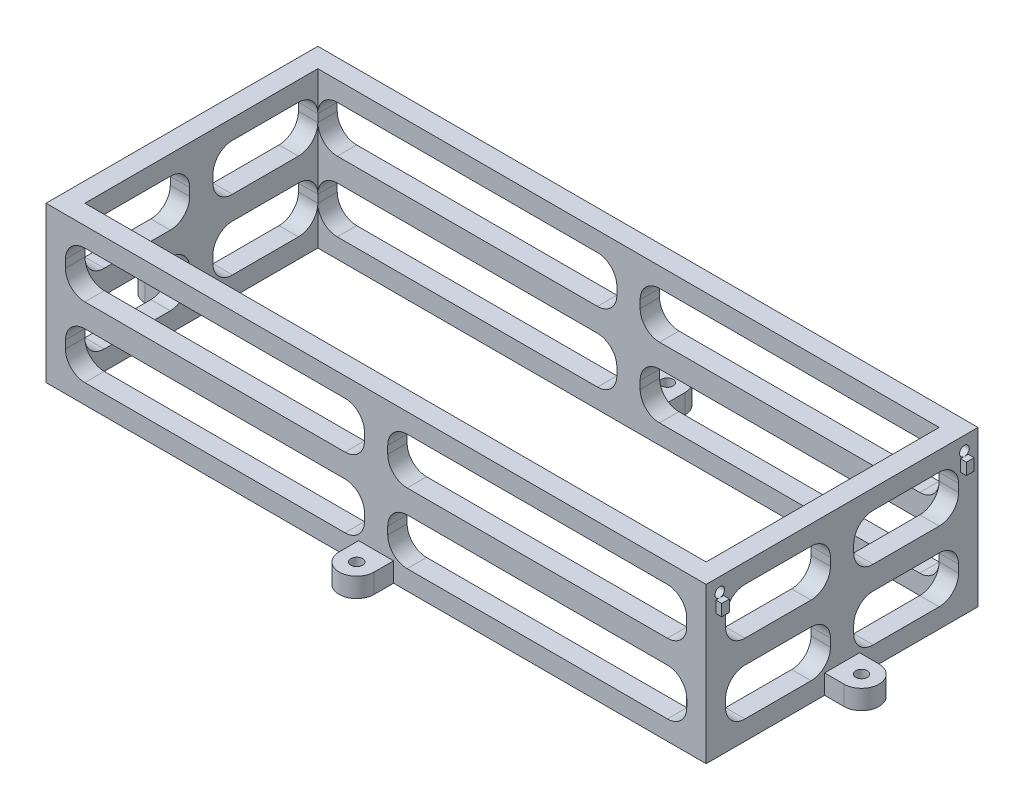
SolidWorks part; units mm, degrees
ref_plane "Front Plane" through (0, 0, 0) normal (0, 0, 1) x (1, 0, 0)
ref_plane "Top Plane" through (0, 0, 0) normal (0, 1, 0) x (1, 0, 0)
ref_plane "Right Plane" through (0, 0, 0) normal (1, 0, 0) x (0, 0, -1)
sketch "Sketch1" plane through (0, 0, 0) normal (0, 1, 0) x (1, 0, 0)
  line L1 (-85, -35) -> (85, -35)
  line L2 (-85, -35) -> (-85, 35)
  line L3 (-85, 35) -> (85, 35)
  line L4 (85, -35) -> (85, 35)
  line L5 (-85, -35) -> (85, 35) construction
  line L6 (-85, 35) -> (85, -35) construction
  point P0 (0, 0)
  dimension "D1" = 70
  dimension "D2" = 170
extrude "Boss-Extrude1" add sketch "Sketch1" along normal blind 40
shell "Shell1" thickness 5
sketch "Sketch3" plane through (-85, 0, 0) normal (-1, 0, 0) x (0, 0, 1)
  line L0 (-35, 20) -> (35, 20) construction
  line L1 (-35, 40) -> (-35, 0) construction
  line L2 (35, 40) -> (35, 0) construction
  line L3 (-35, 40) -> (35, 40) construction
  line L4 (-30, 5) -> (30, 5)
  line L5 (-30, 5) -> (-30, 35)
  line L6 (-30, 35) -> (30, 35)
  line L7 (30, 5) -> (30, 35)
  line L8 (-30, 5) -> (30, 35) construction
  line L9 (-30, 35) -> (30, 5) construction
  point P6 (0, 20)
  dimension "D1" = 5
  dimension "D2" = 5
sketch "Sketch4" plane through (85, 0, 0) normal (1, 0, 0) x (0, 0, -1)
  line L0 (0, 40) -> (0, 0) construction
  line L1 (-35, 40) -> (35, 40) construction
  line L2 (-35, 20) -> (35, 20) construction
  line L3 (-35, 40) -> (-35, 0) construction
  line L4 (35, 40) -> (35, 0) construction
  line L5 (-35, 0) -> (35, 0) construction
  line L6 (-25, 35) -> (-8, 35)
  line L7 (-30, 30) -> (-30, 28)
  line L8 (-25, 23) -> (-8, 23)
  line L9 (-3, 30) -> (-3, 28)
  line L10 (-25, 17) -> (-8, 17)
  line L11 (-30, 12) -> (-30, 10)
  line L12 (-25, 5) -> (-8, 5)
  line L13 (-3, 12) -> (-3, 10)
  line L14 (8, 35) -> (25, 35)
  line L15 (3, 30) -> (3, 28)
  line L16 (8, 23) -> (25, 23)
  line L17 (30, 30) -> (30, 28)
  line L18 (8, 17) -> (25, 17)
  line L19 (3, 12) -> (3, 10)
  line L20 (8, 5) -> (25, 5)
  line L21 (30, 12) -> (30, 10)
  arc A0 (3, 28) -> (8, 23) centre (8, 28) ccw
  arc A1 (8, 17) -> (3, 12) centre (8, 12) ccw
  arc A2 (25, 5) -> (30, 10) centre (25, 10) ccw
  arc A3 (25, 17) -> (30, 12) centre (25, 12) cw
  arc A4 (25, 23) -> (30, 28) centre (25, 28) ccw
  arc A5 (25, 35) -> (30, 30) centre (25, 30) cw
  arc A6 (8, 35) -> (3, 30) centre (8, 30) ccw
  arc A7 (3, 10) -> (8, 5) centre (8, 10) ccw
  arc A8 (-8, 5) -> (-3, 10) centre (-8, 10) ccw
  arc A9 (-8, 17) -> (-3, 12) centre (-8, 12) cw
  arc A10 (-8, 23) -> (-3, 28) centre (-8, 28) ccw
  arc A11 (-8, 35) -> (-3, 30) centre (-8, 30) cw
  arc A12 (-30, 10) -> (-25, 5) centre (-25, 10) ccw
  arc A13 (-25, 17) -> (-30, 12) centre (-25, 12) ccw
  arc A14 (-30, 28) -> (-25, 23) centre (-25, 28) ccw
  arc A15 (-25, 35) -> (-30, 30) centre (-25, 30) ccw
  dimension "D17" = 5
  dimension "D1" = 5
  dimension "D2" = 5
  dimension "D3" = 5
  dimension "D4" = 5
  dimension "D5" = 5
  dimension "D6" = 5
  dimension "D7" = 5
  dimension "D8" = 5
  dimension "D9" = 3
  dimension "D10" = 3
  dimension "D11" = 3
  dimension "D12" = 3
  dimension "D13" = 3
  dimension "D14" = 3
  dimension "D15" = 3
  dimension "D16" = 3
extrude "Cut-Extrude1" cut sketch "Sketch4" against normal blind 170
sketch "Sketch5" plane through (0, 0, 35) normal (0, 0, 1) x (1, 0, 0)
  line L0 (0, 40) -> (0, 0) construction
  line L1 (-85, 40) -> (85, 40) construction
  line L2 (-85, 0) -> (85, 0) construction
  line L3 (-85, 20) -> (85, 20) construction
  line L4 (-85, 40) -> (-85, 0) construction
  line L5 (85, 40) -> (85, 0) construction
  line L7 (-75, 35) -> (-8, 35)
  line L8 (-80, 30) -> (-80, 28)
  line L9 (-75, 23) -> (-8, 23)
  line L10 (-3, 30) -> (-3, 28)
  line L11 (-75, 17) -> (-8, 17)
  line L12 (-80, 12) -> (-80, 10)
  line L13 (-75, 5) -> (-8, 5)
  line L14 (-3, 12) -> (-3, 10)
  line L15 (8, 35) -> (75, 35)
  line L16 (3, 30) -> (3, 28)
  line L17 (8, 23) -> (75, 23)
  line L18 (80, 30) -> (80, 28)
  line L19 (8, 17) -> (75, 17)
  line L20 (3, 12) -> (3, 10)
  line L21 (8, 5) -> (75, 5)
  line L22 (80, 12) -> (80, 10)
  arc A0 (75, 23) -> (80, 28) centre (75, 28) ccw
  arc A1 (75, 35) -> (80, 30) centre (75, 30) cw
  arc A2 (75, 5) -> (80, 10) centre (75, 10) ccw
  arc A3 (80, 12) -> (75, 17) centre (75, 12) ccw
  arc A4 (3, 10) -> (8, 5) centre (8, 10) ccw
  arc A5 (8, 17) -> (3, 12) centre (8, 12) ccw
  arc A6 (3, 28) -> (8, 23) centre (8, 28) ccw
  arc A7 (8, 35) -> (3, 30) centre (8, 30) ccw
  arc A8 (-8, 17) -> (-3, 12) centre (-8, 12) cw
  arc A9 (-8, 5) -> (-3, 10) centre (-8, 10) ccw
  arc A10 (-8, 35) -> (-3, 30) centre (-8, 30) cw
  arc A11 (-80, 10) -> (-75, 5) centre (-75, 10) ccw
  arc A12 (-75, 17) -> (-80, 12) centre (-75, 12) ccw
  arc A13 (-80, 28) -> (-75, 23) centre (-75, 28) ccw
  arc A14 (-75, 35) -> (-80, 30) centre (-75, 30) ccw
  arc A15 (-8, 23) -> (-3, 28) centre (-8, 28) ccw
  dimension "D17" = 5
  dimension "D18" = 5
  dimension "D1" = 5
  dimension "D2" = 5
  dimension "D3" = 5
  dimension "D4" = 5
  dimension "D5" = 5
  dimension "D6" = 5
  dimension "D7" = 5
  dimension "D8" = 5
  dimension "D9" = 3
  dimension "D10" = 3
  dimension "D11" = 3
  dimension "D12" = 3
  dimension "D13" = 3
  dimension "D14" = 3
  dimension "D15" = 3
  dimension "D16" = 3
extrude "Cut-Extrude2" cut sketch "Sketch5" against normal blind 90
sketch "Sketch6" plane through (0, 0, 0) normal (0, -1, 0) x (1, 0, 0)
  line L0 (0, 35) -> (0, -35) construction
  line L1 (-85, 35) -> (85, 35) construction
  line L2 (85, -35) -> (-85, -35) construction
  line L3 (-85, 0) -> (85, 0) construction
  line L4 (-85, -35) -> (-85, 35) construction
  line L5 (85, 35) -> (85, -35) construction
  line L6 (-80, 30) -> (80, 30) construction
  line L7 (4.5, 40) -> (-4.5, 40)
  line L8 (4.5, 40) -> (4.5, 30)
  line L9 (4.5, 30) -> (-4.5, 30)
  line L10 (-4.5, 40) -> (-4.5, 30)
  line L11 (4.5, 40) -> (-4.5, 30) construction
  line L12 (4.5, 30) -> (-4.5, 40) construction
  line L13 (-80, -30) -> (-80, 30) construction
  line L14 (-90, -4.5) -> (-80, -4.5)
  line L15 (-90, -4.5) -> (-90, 4.5)
  line L16 (-90, 4.5) -> (-80, 4.5)
  line L17 (-80, -4.5) -> (-80, 4.5)
  line L18 (-90, -4.5) -> (-80, 4.5) construction
  line L19 (-90, 4.5) -> (-80, -4.5) construction
  line L20 (80, -30) -> (-80, -30) construction
  line L21 (-4.5, -40) -> (4.5, -40)
  line L22 (-4.5, -40) -> (-4.5, -30)
  line L23 (-4.5, -30) -> (4.5, -30)
  line L24 (4.5, -40) -> (4.5, -30)
  line L25 (-4.5, -40) -> (4.5, -30) construction
  line L26 (-4.5, -30) -> (4.5, -40) construction
  line L27 (80, 30) -> (80, -30) construction
  line L28 (90, 4.5) -> (80, 4.5)
  line L29 (90, 4.5) -> (90, -4.5)
  line L30 (90, -4.5) -> (80, -4.5)
  line L31 (80, 4.5) -> (80, -4.5)
  line L32 (90, 4.5) -> (80, -4.5) construction
  line L33 (90, -4.5) -> (80, 4.5) construction
  circle A0 centre (0, 40) radius 4.5
  circle A1 centre (90, 0) radius 4.5
  circle A2 centre (0, -40) radius 4.5
  circle A3 centre (-90, 0) radius 4.5
  circle A4 centre (0, 40) radius 1.5
  circle A5 centre (90, 0) radius 1.5
  circle A6 centre (0, -40) radius 1.5
  circle A7 centre (-90, 0) radius 1.5
  dimension "D5" = 3
  dimension "D6" = 3
  dimension "D7" = 3
  dimension "D8" = 3
  dimension "D1" = 9
  dimension "D2" = 9
  dimension "D3" = 9
  dimension "D4" = 9
extrude "Boss-Extrude2" add sketch "Sketch6" against normal blind 5 contours L15 L14 L17 L16 | A3 | L8 L7 L10 L9 | A0 | L29 L28 L31 L30 | A1 | L22 L21 L24 L23 | A2 | A7
sketch "Sketch7" plane through (0, 0, 0) normal (0, -1, 0) x (1, 0, 0)
  line L0 (-90, -1.5) -> (-90, 1.5) construction
  circle A0 centre (0, 40) radius 1.5
  circle A1 centre (-90, 0) radius 1.5
  circle A2 centre (0, -40) radius 1.5
  circle A3 centre (90, 0) radius 1.5
  dimension "D1" = 3
  dimension "D2" = 3
  dimension "D3" = 3
  dimension "D4" = 3
extrude "Cut-Extrude3" cut sketch "Sketch7" against normal blind 5
sketch "Sketch8" plane through (85, 0, 0) normal (1, 0, 0) x (0, 0, -1)
  line L0 (-35, 40) -> (35, 40) construction
  line L1 (-35, 40) -> (-35, 0) construction
  line L2 (35, 40) -> (35, 0) construction
  circle A0 centre (-31.5, 36.5) radius 1.25
  circle A1 centre (31.5, 36.5) radius 1.25
  dimension "D1" = 2.5
  dimension "D2" = 2.5
  dimension "D3" = 3.5
  dimension "D4" = 3.5
  dimension "D5" = 3.5
  dimension "D6" = 3.5
extrude "Cut-Extrude4" cut sketch "Sketch8" against normal blind 5
sketch "Sketch9" plane through (-85, 0, 0) normal (-1, 0, 0) x (0, 0, 1)
  line L0 (-35, 40) -> (35, 40) construction
  line L1 (-35, 40) -> (-35, 0) construction
  line L2 (35, 40) -> (35, 0) construction
  circle A0 centre (-31.5, 36.5) radius 1.25
  circle A1 centre (31.5, 36.5) radius 1.25
  dimension "D1" = 2.5
  dimension "D2" = 2.5
  dimension "D3" = 3.5
  dimension "D4" = 3.5
  dimension "D5" = 3.5
  dimension "D6" = 3.5
extrude "Cut-Extrude5" cut sketch "Sketch9" against normal blind 5
sketch "Sketch10" plane through (-85, 0, 0) normal (-1, 0, 0) x (0, 0, 1)
  line L0 (-31.5, 36.5) -> (-31.5, 27.4167) construction
  line L1 (31.5, 36.5) -> (31.5, 27.8335) construction
  line L3 (-32.5, 32.25) -> (-30.5, 32.25)
  line L4 (-32.5, 32.25) -> (-32.5, 35.25)
  line L5 (-32.5, 35.25) -> (-30.5, 35.25)
  line L6 (-30.5, 32.25) -> (-30.5, 35.25)
  line L7 (-32.5, 32.25) -> (-30.5, 35.25) construction
  line L8 (-32.5, 35.25) -> (-30.5, 32.25) construction
  line L9 (30.5, 32.25) -> (32.5, 32.25)
  line L10 (30.5, 32.25) -> (30.5, 35.25)
  line L11 (30.5, 35.25) -> (32.5, 35.25)
  line L12 (32.5, 32.25) -> (32.5, 35.25)
  line L13 (30.5, 32.25) -> (32.5, 35.25) construction
  line L14 (30.5, 35.25) -> (32.5, 32.25) construction
  point P6 (-31.5, 33.75)
  point P11 (31.5, 33.75)
  dimension "D1" = 1.25
  dimension "D2" = 2
  dimension "D3" = 3
  dimension "D4" = 1.25
  dimension "D5" = 2
  dimension "D6" = 3
extrude "Boss-Extrude3" add sketch "Sketch10" along normal blind 1.5
sketch "Sketch11" plane through (85, 0, 0) normal (1, 0, 0) x (0, 0, -1)
  line L0 (-31.5, 36.5) -> (-31.5, 31.0757) construction
  line L1 (31.5, 36.5) -> (31.5, 30.4027) construction
  line L3 (-32.5, 32.25) -> (-30.5, 32.25)
  line L4 (-32.5, 32.25) -> (-32.5, 35.25)
  line L5 (-32.5, 35.25) -> (-30.5, 35.25)
  line L6 (-30.5, 32.25) -> (-30.5, 35.25)
  line L7 (-32.5, 32.25) -> (-30.5, 35.25) construction
  line L8 (-32.5, 35.25) -> (-30.5, 32.25) construction
  line L9 (30.5, 32.25) -> (32.5, 32.25)
  line L10 (30.5, 32.25) -> (30.5, 35.25)
  line L11 (30.5, 35.25) -> (32.5, 35.25)
  line L12 (32.5, 32.25) -> (32.5, 35.25)
  line L13 (30.5, 32.25) -> (32.5, 35.25) construction
  line L14 (30.5, 35.25) -> (32.5, 32.25) construction
  point P6 (-31.5, 33.75)
  point P11 (31.5, 33.75)
  dimension "D1" = 1.25
  dimension "D2" = 1.25
  dimension "D3" = 2
  dimension "D4" = 2
  dimension "D5" = 3
  dimension "D6" = 3
extrude "Boss-Extrude4" add sketch "Sketch11" along normal blind 1.5
